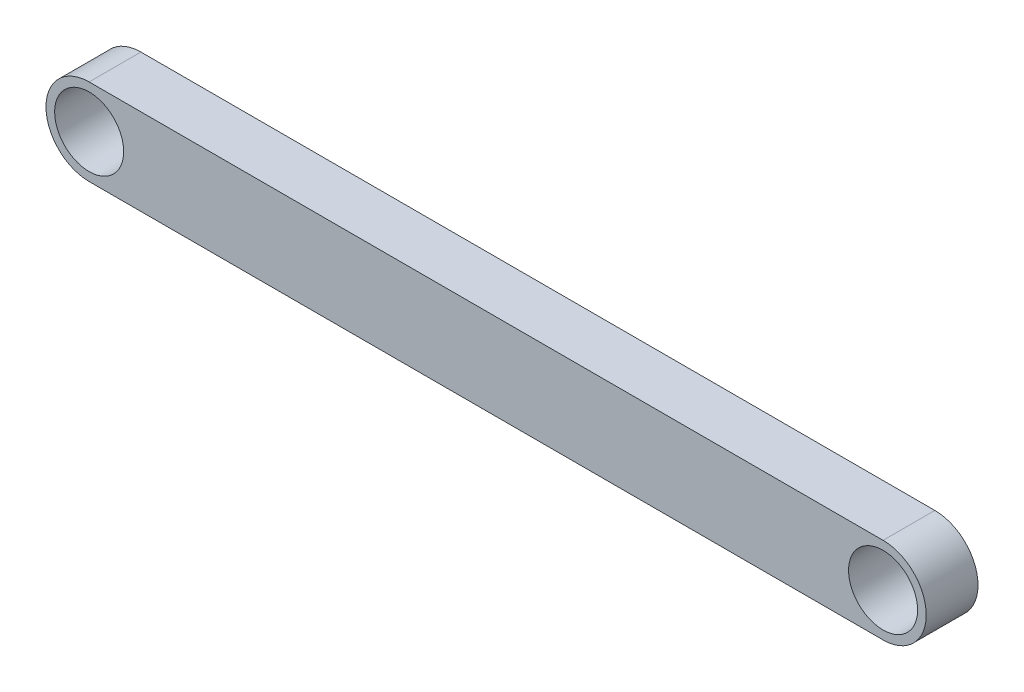
SolidWorks part; units mm, degrees
ref_plane "前视基准面" through (0, 0, 0) normal (0, 0, 1) x (1, 0, 0)
ref_plane "上视基准面" through (0, 0, 0) normal (0, 1, 0) x (1, 0, 0)
ref_plane "右视基准面" through (0, 0, 0) normal (1, 0, 0) x (0, 0, -1)
sketch "草图1" plane through (0, 0, 0) normal (0, 0, 1) x (1, 0, 0)
  line L0 (0, 2.5) -> (-46, 2.5)
  line L1 (-23, 2.5) -> (-23, -1.6096) construction
  line L2 (-46, -2.5) -> (0, -2.5)
  arc A0 (0, -2.5) -> (0, 2.5) centre (0, 0) ccw
  circle A1 centre (0, 0) radius 2
  arc A2 (-46, -2.5) -> (-46, 2.5) centre (-46, 0) cw
  circle A3 centre (-46, 0) radius 2
  dimension "D1" = 5
  dimension "D2" = 4
  dimension "D3" = 46
extrude "凸台-拉伸1" add sketch "草图1" along normal blind 3
